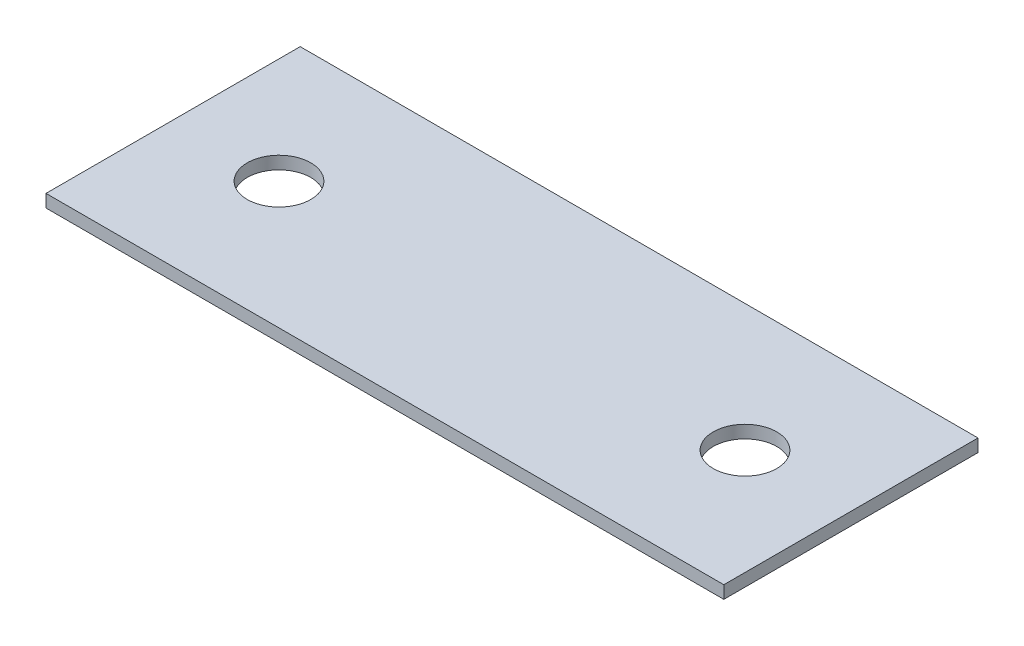
SolidWorks part; units mm, degrees
material "ASTM A36 Steel"
ref_plane "Front Plane" through (0, 0, 0) normal (0, 0, 1) x (1, 0, 0)
ref_plane "Top Plane" through (0, 0, 0) normal (0, 1, 0) x (1, 0, 0)
ref_plane "Right Plane" through (0, 0, 0) normal (1, 0, 0) x (0, 0, -1)
sketch "Sketch1" plane through (0, 0, 0) normal (0, 1, 0) x (1, 0, 0)
  line L1 (-80, 30) -> (80, 30)
  line L2 (-80, 30) -> (-80, -30)
  line L3 (-80, -30) -> (80, -30)
  line L4 (80, 30) -> (80, -30)
  line L5 (-80, 30) -> (80, -30) construction
  line L6 (-80, -30) -> (80, 30) construction
  circle A0 centre (55, 0) radius 7.5
  circle A1 centre (-55, 0) radius 7.5
  point P0 (0, 0)
extrude "Boss-Extrude1" add sketch "Sketch1" along normal blind 3
